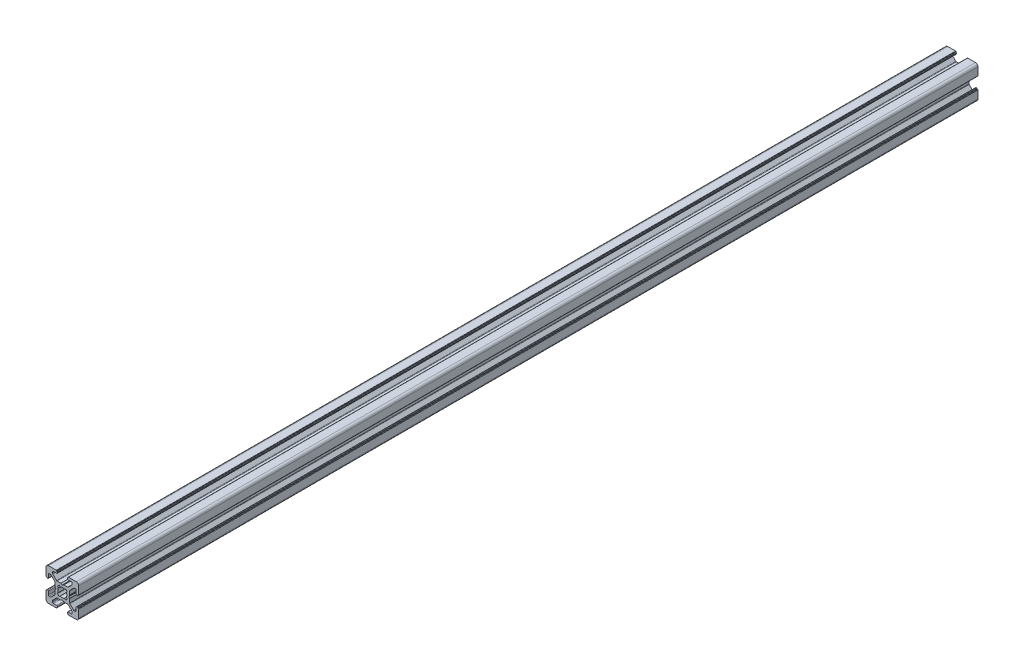
SolidWorks part; units mm, degrees
ref_plane "Front Plane" through (0, 0, 0) normal (0, 0, 1) x (1, 0, 0)
ref_plane "Top Plane" through (0, 0, 0) normal (0, 1, 0) x (1, 0, 0)
ref_plane "Right Plane" through (0, 0, 0) normal (1, 0, 0) x (0, 0, -1)
sketch "Sketch1" plane through (0, 0, 0) normal (0, 0, 1) x (1, 0, 0)
  line L0 (0, 13.3675) -> (0, -10.9159) construction
  line L1 (-12.9725, 0) -> (15.1887, 0) construction
  line L2 (-3.5, 8.5) -> (-5.5, 8.5)
  line L3 (-3.55, 9.7) -> (-3.55, 9.8)
  line L4 (-6, 7.2678) -> (-6, 8)
  line L5 (-7.2678, 6) -> (-8, 6)
  line L6 (-3.75, 10) -> (-8.5, 10)
  line L7 (-9.7, 3.55) -> (-9.8, 3.55)
  line L8 (-9.5, 3.2) -> (-9.5, 3.35)
  line L9 (-9, 3) -> (-9.3, 3)
  line L10 (-4.4732, 0.8536) -> (-4.0381, 0.1)
  line L11 (-4.5, 3.2322) -> (-4.5, 0.9536)
  line L12 (-8.5, 3.5) -> (-8.5, 5.5)
  line L13 (-10, 3.75) -> (-10, 8.5)
  line L14 (-3.5858, 4.6464) -> (-5.8536, 6.9142)
  line L15 (-4.6464, 3.5858) -> (-6.9142, 5.8536)
  line L16 (-3.2, 9.5) -> (-3.35, 9.5)
  line L17 (-3, 9) -> (-3, 9.3)
  line L18 (-0.8536, 4.4732) -> (-0.1, 4.0381)
  line L19 (-3.2322, 4.5) -> (-0.9536, 4.5)
  line L20 (-1.2582, 2.4453) -> (-1.9139, 2.9896)
  line L21 (-2.4453, 1.2582) -> (-2.9922, 1.9099)
  line L22 (3.5, -8.5) -> (5.5, -8.5)
  line L23 (3.55, -9.7) -> (3.55, -9.8)
  line L24 (6, -7.2678) -> (6, -8)
  line L25 (7.2678, -6) -> (8, -6)
  line L26 (3.75, -10) -> (8.5, -10)
  line L27 (9.7, -3.55) -> (9.8, -3.55)
  line L28 (9.5, -3.2) -> (9.5, -3.35)
  line L29 (9, -3) -> (9.3, -3)
  line L30 (4.4732, -0.8536) -> (4.0381, -0.1)
  line L31 (4.5, -3.2322) -> (4.5, -0.9536)
  line L32 (8.5, -3.5) -> (8.5, -5.5)
  line L33 (10, -3.75) -> (10, -8.5)
  line L34 (3.5858, -4.6464) -> (5.8536, -6.9142)
  line L35 (4.6464, -3.5858) -> (6.9142, -5.8536)
  line L36 (3.2, -9.5) -> (3.35, -9.5)
  line L37 (3, -9) -> (3, -9.3)
  line L38 (0.8536, -4.4732) -> (0.1, -4.0381)
  line L39 (3.2322, -4.5) -> (0.9536, -4.5)
  line L40 (1.2582, -2.4453) -> (1.9139, -2.9896)
  line L41 (2.4453, -1.2582) -> (2.9922, -1.9099)
  line L42 (-2.4453, -1.2582) -> (-2.9922, -1.9099)
  line L43 (-1.2582, -2.4453) -> (-1.9139, -2.9896)
  line L44 (-3.2322, -4.5) -> (-0.9536, -4.5)
  line L45 (-0.8536, -4.4732) -> (-0.1, -4.0381)
  line L46 (-3, -9) -> (-3, -9.3)
  line L47 (-3.2, -9.5) -> (-3.35, -9.5)
  line L48 (-4.6464, -3.5858) -> (-6.9142, -5.8536)
  line L49 (-3.5858, -4.6464) -> (-5.8536, -6.9142)
  line L50 (-10, -3.75) -> (-10, -8.5)
  line L51 (-8.5, -3.5) -> (-8.5, -5.5)
  line L52 (-4.5, -3.2322) -> (-4.5, -0.9536)
  line L53 (-4.4732, -0.8536) -> (-4.0381, -0.1)
  line L54 (-9, -3) -> (-9.3, -3)
  line L55 (-9.5, -3.2) -> (-9.5, -3.35)
  line L56 (-9.7, -3.55) -> (-9.8, -3.55)
  line L57 (2.4453, 1.2582) -> (2.9922, 1.9099)
  line L58 (1.2582, 2.4453) -> (1.9139, 2.9896)
  line L59 (3.2322, 4.5) -> (0.9536, 4.5)
  line L60 (0.8536, 4.4732) -> (0.1, 4.0381)
  line L61 (-3.75, -10) -> (-8.5, -10)
  line L62 (-7.2678, -6) -> (-8, -6)
  line L63 (-6, -7.2678) -> (-6, -8)
  line L64 (3, 9) -> (3, 9.3)
  line L65 (3.2, 9.5) -> (3.35, 9.5)
  line L66 (4.6464, 3.5858) -> (6.9142, 5.8536)
  line L67 (3.5858, 4.6464) -> (5.8536, 6.9142)
  line L68 (10, 3.75) -> (10, 8.5)
  line L69 (8.5, 3.5) -> (8.5, 5.5)
  line L70 (4.5, 3.2322) -> (4.5, 0.9536)
  line L71 (4.4732, 0.8536) -> (4.0381, 0.1)
  line L72 (9, 3) -> (9.3, 3)
  line L73 (9.5, 3.2) -> (9.5, 3.35)
  line L74 (9.7, 3.55) -> (9.8, 3.55)
  line L75 (3.75, 10) -> (8.5, 10)
  line L76 (7.2678, 6) -> (8, 6)
  line L77 (6, 7.2678) -> (6, 8)
  line L78 (3.55, 9.7) -> (3.55, 9.8)
  line L79 (3.5, 8.5) -> (5.5, 8.5)
  line L80 (-3.55, -9.7) -> (-3.55, -9.8)
  line L81 (-3.5, -8.5) -> (-5.5, -8.5)
  arc A0 (-10, 8.5) -> (-8.5, 10) centre (-8.5, 8.5) cw
  arc A1 (-8.5, 5.5) -> (-8, 6) centre (-8, 5.5) cw
  arc A2 (-7.2678, 6) -> (-6.9142, 5.8536) centre (-7.2678, 5.5) cw
  arc A3 (-5.8536, 6.9142) -> (-6, 7.2678) centre (-5.5, 7.2678) cw
  arc A4 (-6, 8) -> (-5.5, 8.5) centre (-5.5, 8) cw
  arc A5 (-9.7, 3.55) -> (-9.5, 3.35) centre (-9.7, 3.35) cw
  arc A6 (-9.8, 3.55) -> (-10, 3.75) centre (-9.8, 3.75) cw
  arc A7 (-9.3, 3) -> (-9.5, 3.2) centre (-9.3, 3.2) cw
  arc A8 (-8.5, 3.5) -> (-9, 3) centre (-9, 3.5) cw
  arc A9 (-4.6464, 3.5858) -> (-4.5, 3.2322) centre (-5, 3.2322) cw
  arc A10 (-4.4732, 0.8536) -> (-4.5, 0.9536) centre (-4.3, 0.9536) cw
  arc A11 (-4.0381, 0.1) -> (-4.0381, -0.1) centre (-4.2113, 0) cw
  arc A12 (-3.2, 9.5) -> (-3, 9.3) centre (-3.2, 9.3) cw
  arc A13 (-0.9536, 4.5) -> (-0.8536, 4.4732) centre (-0.9536, 4.3) cw
  arc A14 (-2.9922, 1.9099) -> (-1.9139, 2.9896) centre (0, 0) cw
  arc A15 (-3.2322, 4.5) -> (-3.5858, 4.6464) centre (-3.2322, 5) cw
  arc A16 (-3.75, 10) -> (-3.55, 9.8) centre (-3.75, 9.8) cw
  arc A17 (-3.35, 9.5) -> (-3.55, 9.7) centre (-3.35, 9.7) cw
  arc A18 (2.4453, -1.2582) -> (2.4453, 1.2582) centre (0, 0) ccw
  arc A19 (-3, 9) -> (-3.5, 8.5) centre (-3.5, 9) cw
  arc A20 (-2.4453, -1.2582) -> (-2.4453, 1.2582) centre (0, 0) cw
  arc A21 (10, -8.5) -> (8.5, -10) centre (8.5, -8.5) cw
  arc A22 (8.5, -5.5) -> (8, -6) centre (8, -5.5) cw
  arc A23 (7.2678, -6) -> (6.9142, -5.8536) centre (7.2678, -5.5) cw
  arc A24 (5.8536, -6.9142) -> (6, -7.2678) centre (5.5, -7.2678) cw
  arc A25 (6, -8) -> (5.5, -8.5) centre (5.5, -8) cw
  arc A26 (9.7, -3.55) -> (9.5, -3.35) centre (9.7, -3.35) cw
  arc A27 (9.8, -3.55) -> (10, -3.75) centre (9.8, -3.75) cw
  arc A28 (9.3, -3) -> (9.5, -3.2) centre (9.3, -3.2) cw
  arc A29 (8.5, -3.5) -> (9, -3) centre (9, -3.5) cw
  arc A30 (4.6464, -3.5858) -> (4.5, -3.2322) centre (5, -3.2322) cw
  arc A31 (4.4732, -0.8536) -> (4.5, -0.9536) centre (4.3, -0.9536) cw
  arc A32 (3.2, -9.5) -> (3, -9.3) centre (3.2, -9.3) cw
  arc A33 (-0.1, -4.0381) -> (0.1, -4.0381) centre (0, -4.2113) cw
  arc A34 (0.9536, -4.5) -> (0.8536, -4.4732) centre (0.9536, -4.3) cw
  arc A35 (2.9922, -1.9099) -> (1.9139, -2.9896) centre (0, 0) cw
  arc A36 (1.2582, -2.4453) -> (-1.2582, -2.4453) centre (0, 0) cw
  arc A37 (3.2322, -4.5) -> (3.5858, -4.6464) centre (3.2322, -5) cw
  arc A38 (3.75, -10) -> (3.55, -9.8) centre (3.75, -9.8) cw
  arc A39 (3.35, -9.5) -> (3.55, -9.7) centre (3.35, -9.7) cw
  arc A40 (3, -9) -> (3.5, -8.5) centre (3.5, -9) cw
  arc A41 (-3, -9) -> (-3.5, -8.5) centre (-3.5, -9) ccw
  arc A42 (-3.35, -9.5) -> (-3.55, -9.7) centre (-3.35, -9.7) ccw
  arc A43 (-3.75, -10) -> (-3.55, -9.8) centre (-3.75, -9.8) ccw
  arc A44 (-3.2322, -4.5) -> (-3.5858, -4.6464) centre (-3.2322, -5) ccw
  arc A45 (-2.9922, -1.9099) -> (-1.9139, -2.9896) centre (0, 0) ccw
  arc A46 (-0.9536, -4.5) -> (-0.8536, -4.4732) centre (-0.9536, -4.3) ccw
  arc A47 (-3.2, -9.5) -> (-3, -9.3) centre (-3.2, -9.3) ccw
  arc A48 (-4.4732, -0.8536) -> (-4.5, -0.9536) centre (-4.3, -0.9536) ccw
  arc A49 (3, 9) -> (3.5, 8.5) centre (3.5, 9) ccw
  arc A50 (3.35, 9.5) -> (3.55, 9.7) centre (3.35, 9.7) ccw
  arc A51 (3.75, 10) -> (3.55, 9.8) centre (3.75, 9.8) ccw
  arc A52 (3.2322, 4.5) -> (3.5858, 4.6464) centre (3.2322, 5) ccw
  arc A53 (1.2582, 2.4453) -> (-1.2582, 2.4453) centre (0, 0) ccw
  arc A54 (-4.6464, -3.5858) -> (-4.5, -3.2322) centre (-5, -3.2322) ccw
  arc A55 (-8.5, -3.5) -> (-9, -3) centre (-9, -3.5) ccw
  arc A56 (-9.3, -3) -> (-9.5, -3.2) centre (-9.3, -3.2) ccw
  arc A57 (-9.8, -3.55) -> (-10, -3.75) centre (-9.8, -3.75) ccw
  arc A58 (-9.7, -3.55) -> (-9.5, -3.35) centre (-9.7, -3.35) ccw
  arc A59 (-6, -8) -> (-5.5, -8.5) centre (-5.5, -8) ccw
  arc A60 (2.9922, 1.9099) -> (1.9139, 2.9896) centre (0, 0) ccw
  arc A61 (0.9536, 4.5) -> (0.8536, 4.4732) centre (0.9536, 4.3) ccw
  arc A62 (-0.1, 4.0381) -> (0.1, 4.0381) centre (0, 4.2113) ccw
  arc A63 (-5.8536, -6.9142) -> (-6, -7.2678) centre (-5.5, -7.2678) ccw
  arc A64 (-7.2678, -6) -> (-6.9142, -5.8536) centre (-7.2678, -5.5) ccw
  arc A65 (-8.5, -5.5) -> (-8, -6) centre (-8, -5.5) ccw
  arc A66 (-10, -8.5) -> (-8.5, -10) centre (-8.5, -8.5) ccw
  arc A67 (3.2, 9.5) -> (3, 9.3) centre (3.2, 9.3) ccw
  arc A68 (4.0381, 0.1) -> (4.0381, -0.1) centre (4.2113, 0) ccw
  arc A69 (4.4732, 0.8536) -> (4.5, 0.9536) centre (4.3, 0.9536) ccw
  arc A70 (4.6464, 3.5858) -> (4.5, 3.2322) centre (5, 3.2322) ccw
  arc A71 (8.5, 3.5) -> (9, 3) centre (9, 3.5) ccw
  arc A72 (9.3, 3) -> (9.5, 3.2) centre (9.3, 3.2) ccw
  arc A73 (9.8, 3.55) -> (10, 3.75) centre (9.8, 3.75) ccw
  arc A74 (9.7, 3.55) -> (9.5, 3.35) centre (9.7, 3.35) ccw
  arc A75 (6, 8) -> (5.5, 8.5) centre (5.5, 8) ccw
  arc A76 (5.8536, 6.9142) -> (6, 7.2678) centre (5.5, 7.2678) ccw
  arc A77 (7.2678, 6) -> (6.9142, 5.8536) centre (7.2678, 5.5) ccw
  arc A78 (8.5, 5.5) -> (8, 6) centre (8, 5.5) ccw
  arc A79 (10, 8.5) -> (8.5, 10) centre (8.5, 8.5) ccw
  dimension "D4" = 5.5
  dimension "D1" = 6
  dimension "D2" = 20
  dimension "D3" = 20
  dimension "D5" = 5.5
  dimension "D6" = 10
  dimension "D7" = 6
  dimension "D8" = 6
  dimension "D9" = 6
extrude "Extrude1" add sketch "Sketch1" along normal blind 550
